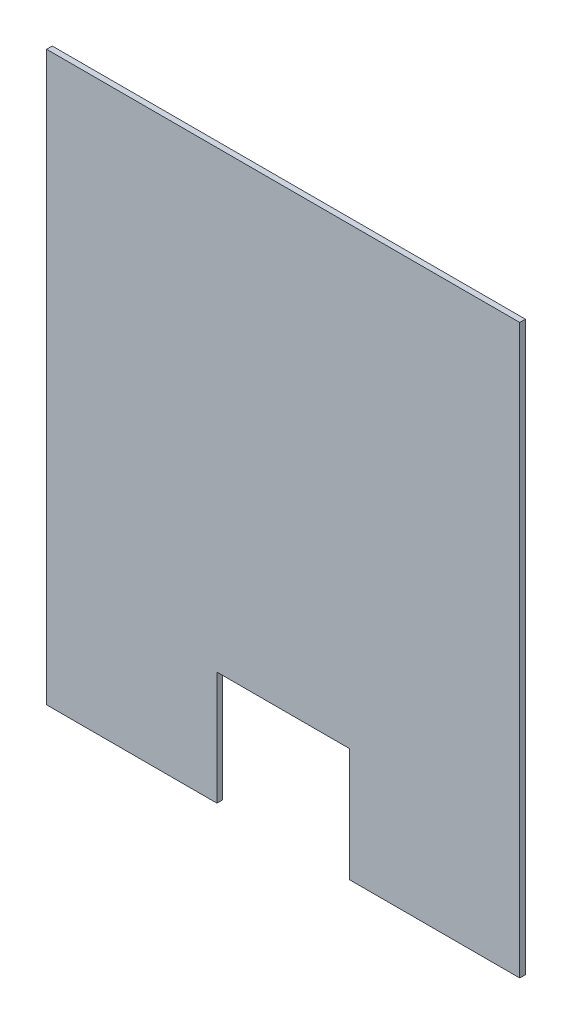
SolidWorks part; units mm, degrees
ref_plane "Plan de face" through (0, 0, 0) normal (0, 0, 1) x (1, 0, 0)
ref_plane "Plan de dessus" through (0, 0, 0) normal (0, 1, 0) x (1, 0, 0)
ref_plane "Plan de droite" through (0, 0, 0) normal (1, 0, 0) x (0, 0, -1)
sketch "Esquisse1" plane through (0, 0, 0) normal (0, 0, 1) x (1, 0, 0)
  line L0 (35, -150) -> (125, -150)
  line L1 (-125, -150) -> (-35, -150)
  line L2 (-125, -150) -> (-125, 150)
  line L3 (-125, 150) -> (125, 150)
  line L4 (125, -150) -> (125, 150)
  line L5 (-125, -150) -> (125, 150) construction
  line L6 (-125, 150) -> (125, -150) construction
  line L8 (-35, -150) -> (-35, -90)
  line L9 (-35, -90) -> (35, -90)
  line L10 (35, -150) -> (35, -90)
  point P0 (0, 0)
  point P6 (0, -150)
  point P8 (0, 0)
  dimension "D1" = 250
  dimension "D2" = 300
  dimension "D3" = 90
  dimension "D4" = 70
  dimension "D5" = 60
extrude "Boss.-Extru.1" add sketch "Esquisse1" along normal blind 3
